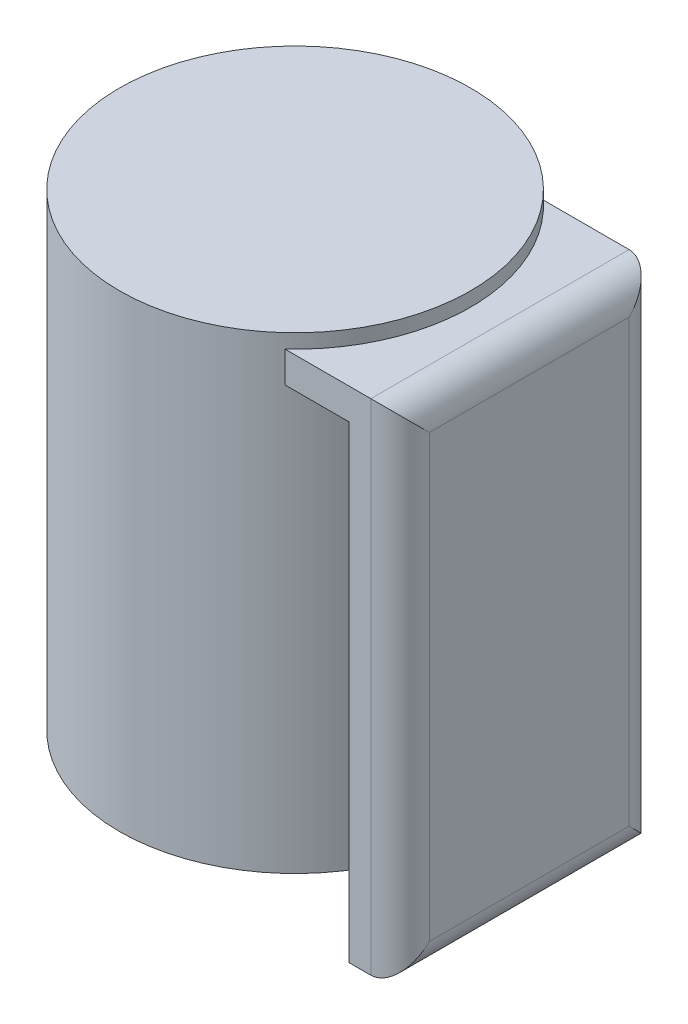
SolidWorks part; units mm, degrees
material "PVC 0.007 Plasticized"
ref_plane "Front Plane" through (0, 0, 0) normal (0, 0, 1) x (1, 0, 0)
ref_plane "Top Plane" through (0, 0, 0) normal (0, 1, 0) x (1, 0, 0)
ref_plane "Right Plane" through (0, 0, 0) normal (1, 0, 0) x (0, 0, -1)
sketch "Sketch2" plane through (0, 0, 0) normal (0, 1, 0) x (1, 0, 0)
  circle A0 centre (0, 0) radius 12.5
  circle A1 centre (0, 0) radius 15
extrude "Boss-Extrude1" add sketch "Sketch2" along normal blind 35
ref_plane "Plane1" through (0, 35, 0) normal (0, 1, 0) x (1, 0, 0)
sketch "Sketch3" plane through (0, 35, 0) normal (0, 1, 0) x (1, 0, 0)
  circle A0 centre (0, 0) radius 15
extrude "Boss-Extrude2" add sketch "Sketch3" along normal blind 5
ref_plane "Plane2" through (10, 0, 0) normal (1, 0, 0) x (0, 0, -1)
sketch "Sketch4" plane through (10, 0, 0) normal (1, 0, 0) x (0, 0, -1)
  line L1 (-11.0281, 38.785) -> (11.0281, 38.785)
  line L2 (-11.0281, 38.785) -> (-11.0281, 36.135)
  line L3 (-11.0281, 36.135) -> (11.0281, 36.135)
  line L4 (11.0281, 38.785) -> (11.0281, 36.135)
  line L5 (-11.0281, 38.785) -> (11.0281, 36.135) construction
  line L6 (-11.0281, 36.135) -> (11.0281, 38.785) construction
  point P0 (0, 37.46)
extrude "Boss-Extrude3" add sketch "Sketch4" along normal blind 10
sketch "Sketch5" plane through (0, 36.135, 0) normal (0, -1, 0) x (1, 0, 0)
  line L1 (15.6144, 11.0281) -> (20, 11.0281)
  line L2 (15.6144, 11.0281) -> (15.6144, -11.0281)
  line L3 (15.6144, -11.0281) -> (20, -11.0281)
  line L4 (20, 11.0281) -> (20, -11.0281)
  line L5 (15.6144, 11.0281) -> (20, -11.0281) construction
  line L6 (15.6144, -11.0281) -> (20, 11.0281) construction
  point P0 (17.8072, 0)
extrude "Boss-Extrude4" add sketch "Sketch5" along normal blind 40
fillet "Fillet1" radius 2.5 4 edges at (20, -3.865, 0) (20, 17.46, 11.0281) (20, 38.785, 0) (20, 17.46, -11.0281)
